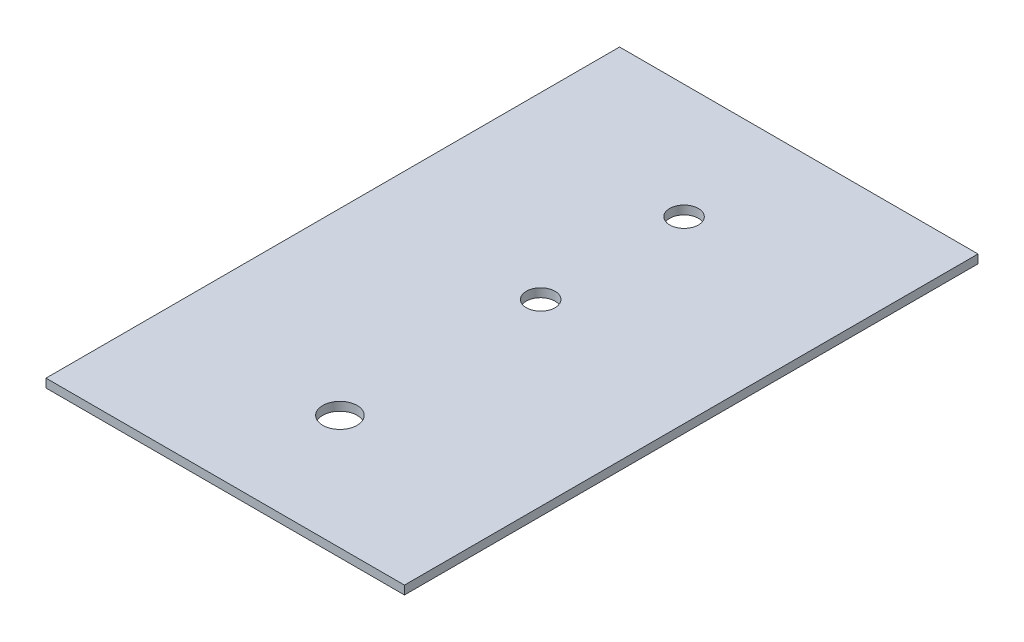
SolidWorks part; units mm, degrees
ref_plane "Front Plane" through (0, 0, 0) normal (0, 0, 1) x (1, 0, 0)
ref_plane "Top Plane" through (0, 0, 0) normal (0, 1, 0) x (1, 0, 0)
ref_plane "Right Plane" through (0, 0, 0) normal (1, 0, 0) x (0, 0, -1)
sketch "Sketch1" plane through (0, 0, 0) normal (0, 1, 0) x (1, 0, 0)
  line L1 (-62.5, -100) -> (62.5, -100)
  line L2 (-62.5, -100) -> (-62.5, 100)
  line L3 (-62.5, 100) -> (62.5, 100)
  line L4 (62.5, -100) -> (62.5, 100)
  line L5 (-62.5, -100) -> (62.5, 100) construction
  line L6 (-62.5, 100) -> (62.5, -100) construction
  point P0 (0, 0)
  dimension "D1" = 125
  dimension "D2" = 200
extrude "Boss-Extrude1" add sketch "Sketch1" along normal blind 3
sketch "Sketch2" plane through (0, 3, 0) normal (0, 1, 0) x (1, 0, 0)
  line L0 (0, 100) -> (0, -100) construction
  line L1 (62.5, 100) -> (-62.5, 100) construction
  line L2 (-62.5, -100) -> (62.5, -100) construction
  circle A0 centre (0, 60) radius 5
  circle A1 centre (0, -60) radius 6
  circle A2 centre (0, 10) radius 5
  dimension "D1" = 10
  dimension "D2" = 10
  dimension "D3" = 12
  dimension "D4" = 40
  dimension "D5" = 90
  dimension "D6" = 160
extrude "Cut-Extrude1" cut sketch "Sketch2" along direction (0, -1, 0) on the side against the normal up to next (3 mm away)
